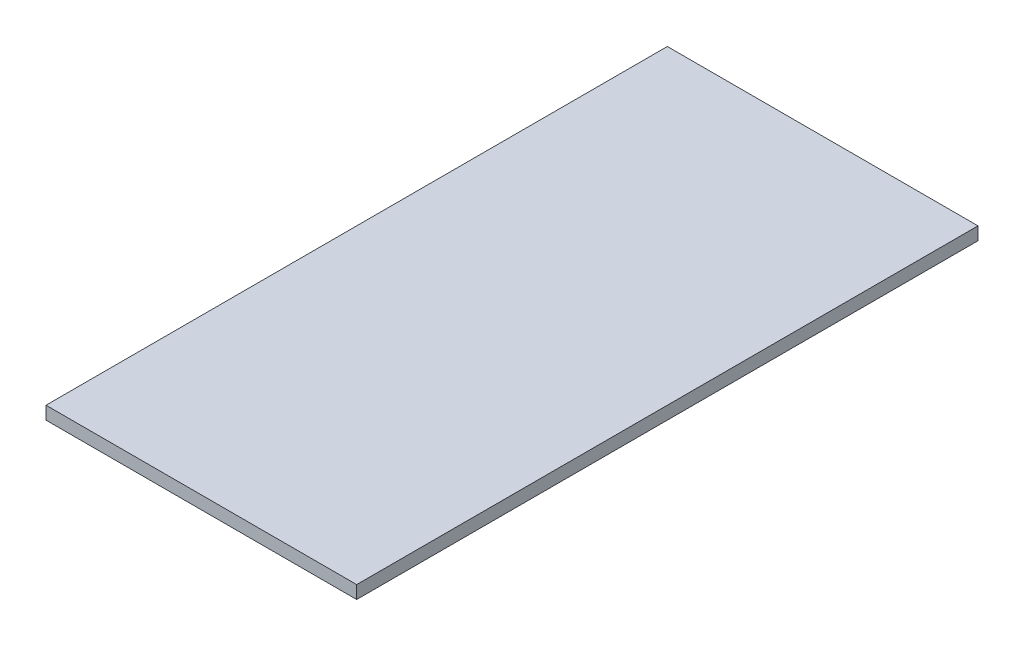
SolidWorks part; units mm, degrees
ref_plane "Front Plane" through (0, 0, 0) normal (0, 0, 1) x (1, 0, 0)
ref_plane "Top Plane" through (0, 0, 0) normal (0, 1, 0) x (1, 0, 0)
ref_plane "Right Plane" through (0, 0, 0) normal (1, 0, 0) x (0, 0, -1)
sketch "Sketch1" plane through (0, 0, 0) normal (0, 1, 0) x (1, 0, 0)
  line L1 (-76.2, -152.4) -> (76.2, -152.4)
  line L2 (-76.2, -152.4) -> (-76.2, 152.4)
  line L3 (-76.2, 152.4) -> (76.2, 152.4)
  line L4 (76.2, -152.4) -> (76.2, 152.4)
  line L5 (-76.2, -152.4) -> (76.2, 152.4) construction
  line L6 (-76.2, 152.4) -> (76.2, -152.4) construction
  point P0 (0, 0)
  dimension "D1" = 304.8
  dimension "D2" = 152.4
extrude "Boss-Extrude1" add sketch "Sketch1" along normal blind 6.35
